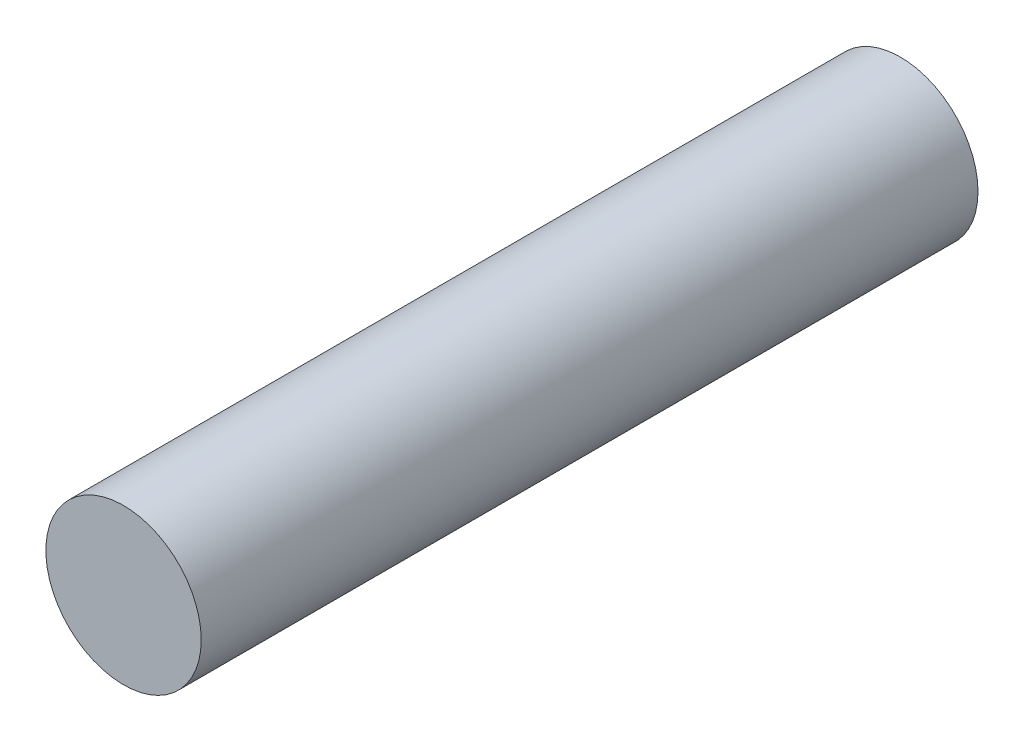
SolidWorks part; units mm, degrees
ref_plane "Front Plane" through (0, 0, 0) normal (0, 0, 1) x (1, 0, 0)
ref_plane "Top Plane" through (0, 0, 0) normal (0, 1, 0) x (1, 0, 0)
ref_plane "Right Plane" through (0, 0, 0) normal (1, 0, 0) x (0, 0, -1)
sketch "Sketch2" plane through (0, 0, 0) normal (0, 0, 1) x (1, 0, 0)
  circle A0 centre (0, 0) radius 3.175
  dimension "D1" = 6.35
extrude "Boss-Extrude1" add sketch "Sketch2" along normal blind 31.75
